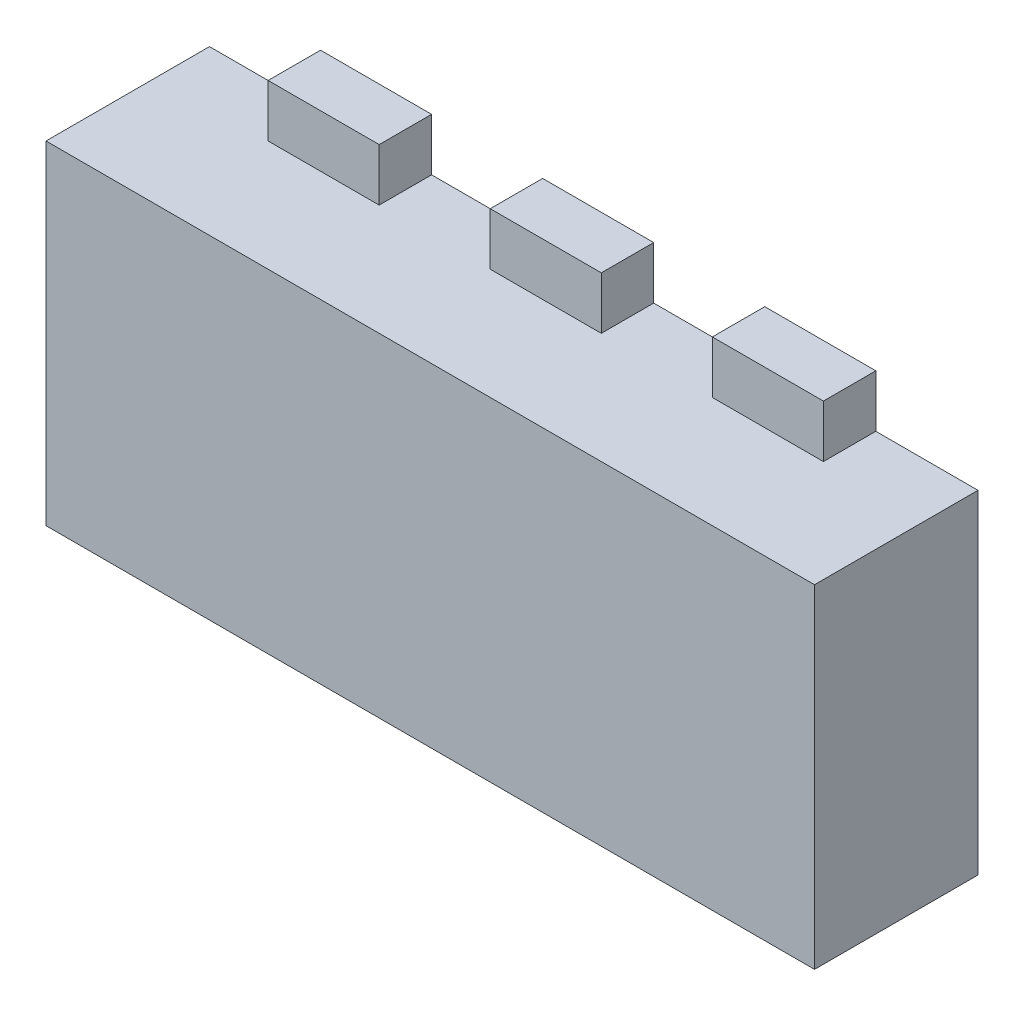
SolidWorks part; units mm, degrees
ref_plane "Front Plane" through (0, 0, 0) normal (0, 0, 1) x (1, 0, 0)
ref_plane "Top Plane" through (0, 0, 0) normal (0, 1, 0) x (1, 0, 0)
ref_plane "Right Plane" through (0, 0, 0) normal (1, 0, 0) x (0, 0, -1)
sketch "Sketch1" plane through (0, 0, 0) normal (0, 0, 1) x (1, 0, 0)
  line L1 (-21.971, -9.525) -> (21.971, -9.525)
  line L2 (-21.971, -9.525) -> (-21.971, 9.525)
  line L3 (-21.971, 9.525) -> (21.971, 9.525)
  line L4 (21.971, -9.525) -> (21.971, 9.525)
  line L5 (-21.971, -9.525) -> (21.971, 9.525) construction
  line L6 (-21.971, 9.525) -> (21.971, -9.525) construction
  point P0 (0, 0)
  dimension "D1" = 19.05
  dimension "D2" = 43.942
extrude "Body" add sketch "Sketch1" along normal blind 2.9972
sketch "Sketch2" plane through (0, 9.525, 0) normal (0, 1, 0) x (1, 0, 0)
  line L0 (21.971, 0) -> (-21.971, 0) construction
  line L1 (-15.621, 0) -> (-9.271, 0)
  line L2 (-15.621, 0) -> (-15.621, -2.9972)
  line L3 (-15.621, -2.9972) -> (-9.271, -2.9972)
  line L4 (-9.271, 0) -> (-9.271, -2.9972)
  line L5 (21.971, -2.9972) -> (-21.971, -2.9972) construction
  line L6 (-21.971, -2.9972) -> (-21.971, 0) construction
  dimension "D1" = 6.35
  dimension "D2" = 6.35
extrude "Tab" add sketch "Sketch2" along normal blind 2.9972
sketch "Sketch3" plane through (0, 0, 2.9972) normal (0, 0, 1) x (1, 0, 0)
  line L0 (-14.859, 12.5222) -> (-14.859, 8.255)
  line L1 (-15.621, 12.5222) -> (-9.271, 12.5222) construction
  line L2 (-14.859, 8.255) -> (-14.224, 8.255)
  line L3 (-14.224, 8.255) -> (-14.224, 12.5222)
  line L4 (-15.621, 9.525) -> (-9.271, 9.525) construction
  line L5 (-12.446, 9.525) -> (-12.446, 12.5222) construction
  line L6 (-14.859, 12.5222) -> (-14.224, 12.5222)
  line L7 (-10.033, 12.5222) -> (-10.668, 12.5222)
  line L8 (-10.668, 8.255) -> (-10.668, 12.5222)
  line L9 (-10.033, 8.255) -> (-10.668, 8.255)
  line L10 (-10.033, 12.5222) -> (-10.033, 8.255)
  line L11 (-8.636, 9.525) -> (-8.636, 8.255)
  line L12 (-15.621, 9.525) -> (-16.256, 9.525)
  line L13 (-15.621, 9.525) -> (-15.621, 8.255)
  line L14 (-15.621, 8.255) -> (-16.256, 8.255)
  line L15 (-16.256, 9.525) -> (-16.256, 8.255)
  line L16 (-9.271, 8.255) -> (-8.636, 8.255)
  line L17 (-9.271, 9.525) -> (-9.271, 8.255)
  line L18 (-9.271, 9.525) -> (-8.636, 9.525)
  line L19 (-15.621, 12.5222) -> (-15.621, 9.525) construction
  dimension "D1" = 0.635
  dimension "D2" = 0.635
  dimension "D3" = 1.27
  dimension "D4" = 0.762
extrude "Slots" [suppressed] cut sketch "Sketch3" against normal through all
fillet "Fillet1" [suppressed] radius 0.254
ref_plane "Tab Midplane" [suppressed] through (-12.7, 0, 0) normal (-1, 0, 0) x (0, 0, 1)
ref_plane "Body Horizontal Midplane" through (0, 0, 0) normal (0, 1, 0) x (1, 0, 0)
ref_plane "Body Vertical Midplane" through (0, 0, 0) normal (-1, 0, 0) x (0, 0, 1)
pattern_linear "LPattern1" count 3 spacing 12.7 along (1, 0, 0) of "Tab"
mirror "Mirror1" about plane through (0, 0, 0) normal (0, 1, 0) of "LPattern1", "Tab"
sketch "Sketch5" plane through (0, 0, 2.9972) normal (0, 0, 1) x (1, 0, 0)
  line L1 (-21.971, 9.525) -> (21.971, 9.525)
  line L2 (-21.971, 9.525) -> (-21.971, -9.525)
  line L3 (-21.971, -9.525) -> (21.971, -9.525)
  line L4 (21.971, 9.525) -> (21.971, -9.525)
extrude "Boss-Extrude1" add sketch "Sketch5" along normal blind 6.35
